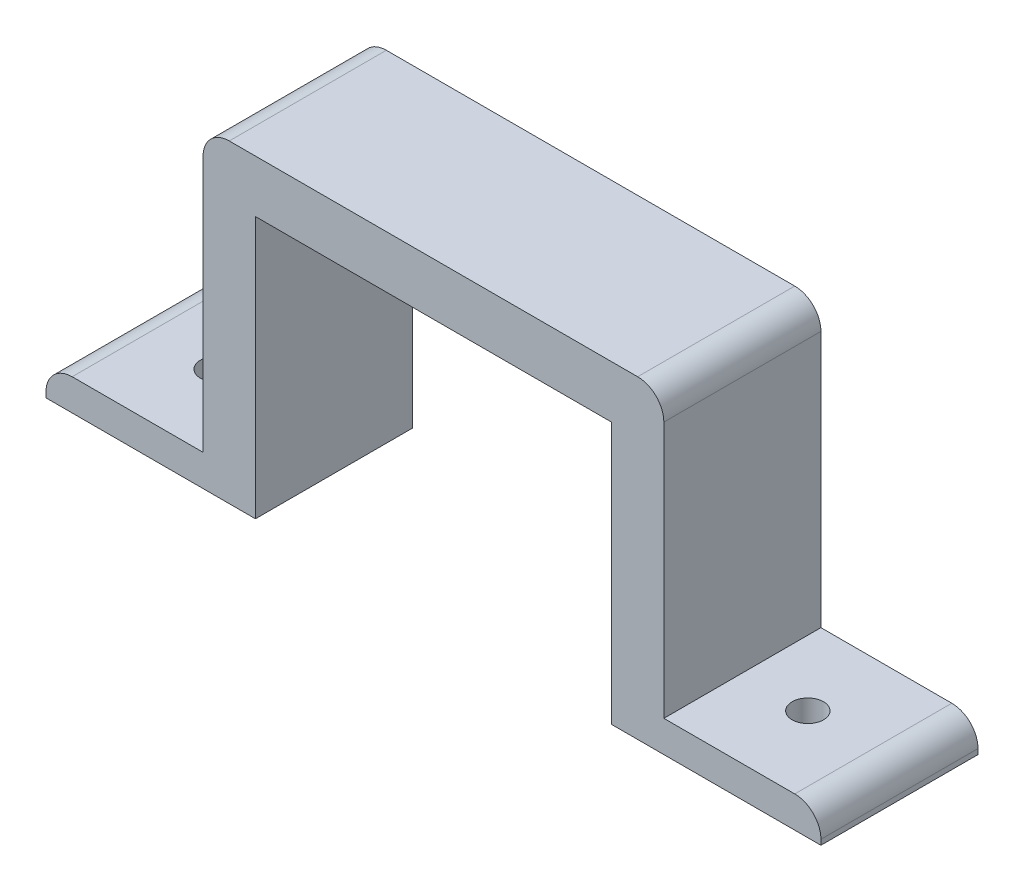
SolidWorks part; units mm, degrees
ref_plane "Front Plane" through (0, 0, 0) normal (0, 0, 1) x (1, 0, 0)
ref_plane "Top Plane" through (0, 0, 0) normal (0, 1, 0) x (1, 0, 0)
ref_plane "Right Plane" through (0, 0, 0) normal (1, 0, 0) x (0, 0, -1)
sketch "Sketch1" plane through (0, 0, 0) normal (0, 0, 1) x (1, 0, 0)
  line L0 (0, 0) -> (0, 25) construction
  line L1 (17, 25) -> (-17, 25)
  line L2 (-17, 25) -> (-17, 0)
  line L3 (-17, 0) -> (-37, 0)
  line L4 (-37, 0) -> (-37, 3)
  line L5 (-37, 3) -> (-22, 3)
  line L6 (-22, 3) -> (-22, 30)
  line L7 (-22, 30) -> (22, 30)
  line L8 (22, 3) -> (22, 30)
  line L9 (37, 3) -> (22, 3)
  line L10 (37, 0) -> (37, 3)
  line L11 (17, 25) -> (17, 0)
  line L12 (17, 0) -> (37, 0)
  point P12 (0, 30)
  dimension "D1" = 30
  dimension "D2" = 25
  dimension "D3" = 3
  dimension "D4" = 17
  dimension "D5" = 22
  dimension "D6" = 37
extrude "Boss-Extrude1" add sketch "Sketch1" along normal blind 15
fillet "Fillet1" radius 2.5 4 edges at (-37, 3, 7.5) (-22, 30, 7.5) (22, 30, 7.5) (37, 3, 7.5)
sketch "Sketch2" plane through (0, 3, 0) normal (0, 1, 0) x (1, 0, 0)
  line L0 (-28.25, 0) -> (-28.25, -15) construction
  line L1 (-22, 0) -> (-34.5, 0) construction
  line L2 (-22, -15) -> (-34.5, -15) construction
  line L3 (0, 0) -> (0, -15) construction
  line L4 (19.5, -15) -> (-19.5, -15) construction
  circle A0 centre (-28.25, -7.5) radius 1.5
  circle A1 centre (28.25, -7.5) radius 1.5
  dimension "D1" = 3
extrude "Cut-Extrude1" cut sketch "Sketch2" against normal up to surface (3 mm away) up to face at (-27, 0, 7.5)
